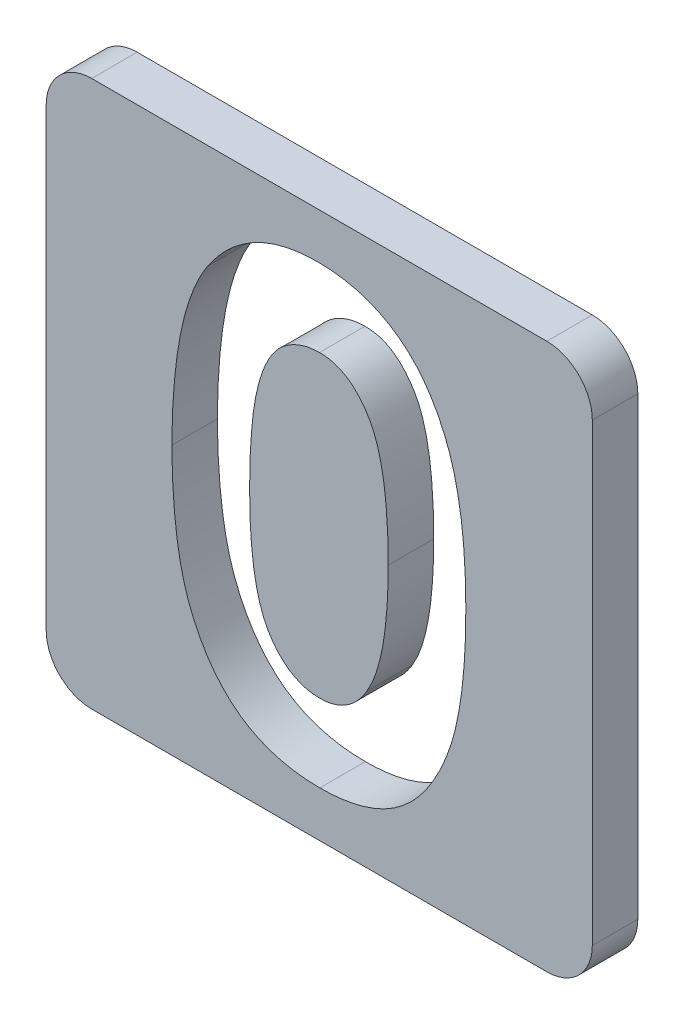
SolidWorks part; units mm, degrees
ref_plane "Front Plane" through (0, 0, 0) normal (0, 0, 1) x (1, 0, 0)
ref_plane "Top Plane" through (0, 0, 0) normal (0, 1, 0) x (1, 0, 0)
ref_plane "Right Plane" through (0, 0, 0) normal (1, 0, 0) x (0, 0, -1)
sketch "Sketch1" plane through (0, 0, 0) normal (0, 0, 1) x (1, 0, 0)
  line L1 (-50, 60) -> (50, 60)
  line L2 (-60, 50) -> (-60, -50)
  line L3 (-50, -60) -> (50, -60)
  line L4 (60, 50) -> (60, -50)
  line L5 (-60, 60) -> (60, -60) construction
  line L6 (-60, -60) -> (60, 60) construction
  arc A0 (-60, -50) -> (-50, -60) centre (-50, -50) ccw
  arc A1 (50, -60) -> (60, -50) centre (50, -50) ccw
  arc A2 (50, 60) -> (60, 50) centre (50, 50) cw
  arc A3 (-50, 60) -> (-60, 50) centre (-50, 50) ccw
  point P0 (0, 0)
  dimension "D3" = 10
  dimension "D1" = 120
  dimension "D2" = 120
extrude "Boss-Extrude1" add sketch "Sketch1" along normal blind 10 contours A3 L2 A0 L3 A1 L4 A2 L1
sketch "Sketch2" plane through (0, 0, 10) normal (0, 0, 1) x (1, 0, 0)
  line L0 (0, 0) -> (0, 40) construction
  line L1 (-50, 50) -> (50, 50) construction
  line L2 (-50, 50) -> (-50, -50) construction
  line L3 (-50, -50) -> (50, -50) construction
  line L4 (50, 50) -> (50, -50) construction
  line L5 (-50, 50) -> (50, -50) construction
  line L6 (-50, -50) -> (50, 50) construction
  line L7 (0, 40) -> (-40, 40) construction
  line L8 (-40, 40) -> (-40, 0) construction
  line L9 (-40, 0) -> (0, 0) construction
  line L11 (0, 20) -> (-20, 20) construction
  line L12 (-20, 40) -> (-20, 20) construction
  circle A0 centre (0, 40) radius 4 construction
  circle A1 centre (0, 20) radius 4 construction
  circle A2 centre (0, 0) radius 4 construction
  circle A3 centre (-20, 20) radius 4 construction
  circle A4 centre (-20, 40) radius 4 construction
  circle A5 centre (-40, 40) radius 4 construction
  circle A6 centre (0, 0) radius 4 construction
  circle A7 centre (20, 0) radius 4 construction
  circle A8 centre (40, 0) radius 4 construction
  circle A9 centre (40, 20) radius 4 construction
  circle A10 centre (40, 40) radius 4 construction
  circle A11 centre (20, 20) radius 4 construction
  circle A12 centre (0, 0) radius 4 construction
  circle A13 centre (0, -20) radius 4 construction
  circle A14 centre (0, -40) radius 4 construction
  circle A15 centre (20, -40) radius 4 construction
  circle A16 centre (40, -40) radius 4 construction
  circle A17 centre (20, -20) radius 4 construction
  circle A18 centre (0, 0) radius 4 construction
  circle A19 centre (-20, 0) radius 4 construction
  circle A20 centre (-40, 0) radius 4 construction
  circle A21 centre (-40, -20) radius 4 construction
  circle A22 centre (-40, -40) radius 4 construction
  circle A23 centre (-20, -20) radius 4 construction
  text T0 "0" font "Century Gothic" height 95
  point P0 (0, 0)
  point P55 (0, 0)
  dimension "D4" = 8
  dimension "D1" = 100
  dimension "D2" = 100
  dimension "D3" = 40
  dimension "D5" = 4
extrude "Cut-Extrude9" cut sketch "Sketch2" against normal blind 10
